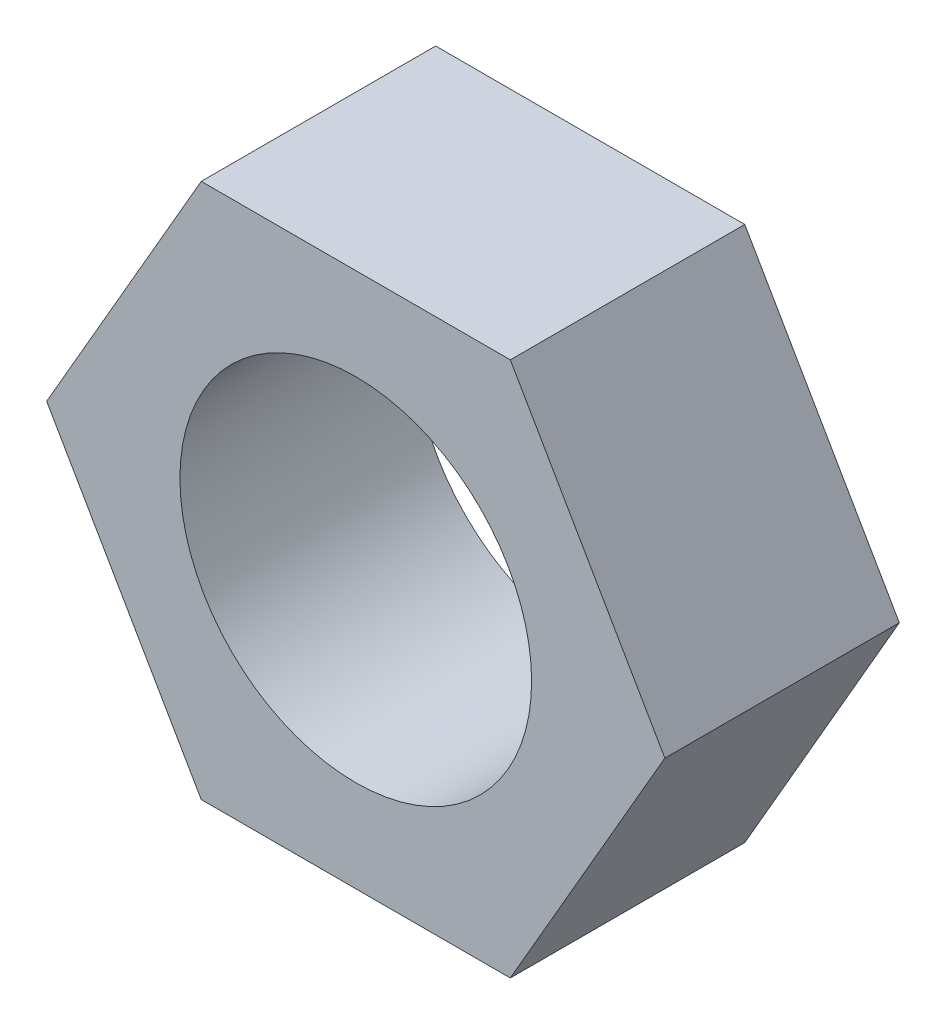
SolidWorks part; units mm, degrees
ref_plane "正面" through (0, 0, 0) normal (0, 0, 1) x (1, 0, 0)
ref_plane "平面" through (0, 0, 0) normal (0, 1, 0) x (1, 0, 0)
ref_plane "右側面" through (0, 0, 0) normal (1, 0, 0) x (0, 0, -1)
sketch "ｽｹｯﾁ1" plane through (0, 0, 0) normal (0, 0, 1) x (1, 0, 0)
  line L1 (3.9548, 0) -> (1.9774, 3.425)
  line L2 (1.9774, 3.425) -> (-1.9774, 3.425)
  line L3 (-1.9774, 3.425) -> (-3.9548, 0)
  line L4 (-3.9548, 0) -> (-1.9774, -3.425)
  line L5 (-1.9774, -3.425) -> (1.9774, -3.425)
  line L6 (1.9774, -3.425) -> (3.9548, 0)
  circle A0 centre (0, 0) radius 3.425 construction
  dimension "D1" = 6.85
extrude "ﾎﾞｽ - 押し出し1" add sketch "ｽｹｯﾁ1" along normal blind 3
hole_wizard "M4 すきま穴1" positions "ｽｹｯﾁ3" profile "ｽｹｯﾁ4" hole size "M4" standard "JIS"
sketch "ｽｹｯﾁ3" plane through (0, 0, 3) normal (0, 0, 1) x (1, 0, 0)
  point P0 (0, 0)
sketch "ｽｹｯﾁ4" plane through (0, 0, 3) normal (1, 0, 0) x (0, -1, 0)
  line L0 (0, 0) -> (0, 21.3519)
  line L1 (0, 21.3519) -> (2.25, 20)
  line L2 (2.25, 20) -> (2.25, 0)
  line L5 (2.25, 0) -> (0, 0)
  line L10 (0, 21.3519) -> (-2.25, 20) construction
  line L11 (0, -6.35) -> (0, 107.95) construction
  dimension "穴の直径" = 4.5
  dimension "穴の深さ" = 20
  dimension "ﾄﾞﾘﾙ角度" = 118
